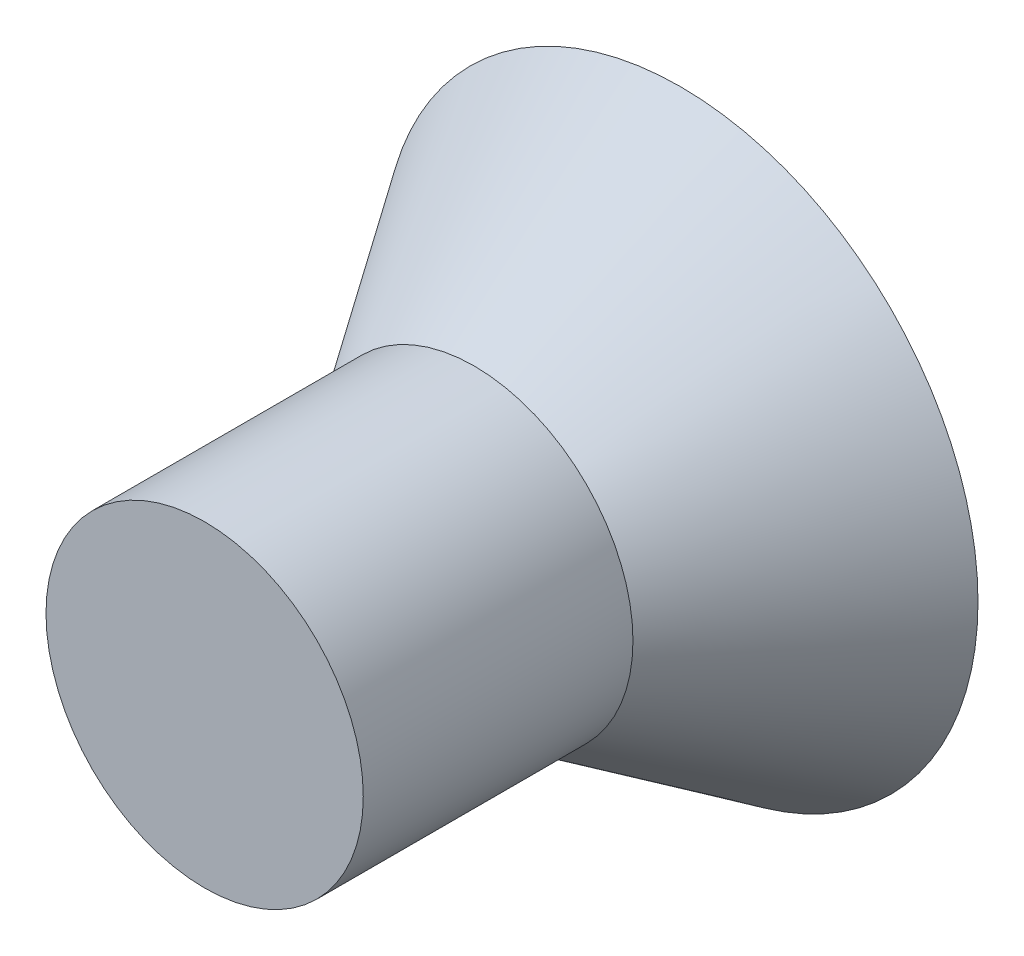
SolidWorks part; units mm, degrees
ref_plane "前视基准面" through (0, 0, 0) normal (0, 0, 1) x (1, 0, 0)
ref_plane "上视基准面" through (0, 0, 0) normal (0, 1, 0) x (1, 0, 0)
ref_plane "右视基准面" through (0, 0, 0) normal (1, 0, 0) x (0, 0, -1)
sketch "草图1" plane through (0, 0, 0) normal (0, 0, 1) x (1, 0, 0)
  circle A0 centre (0, 0) radius 2
  dimension "D1" = 4
extrude "凸台-拉伸1" add sketch "草图1" along normal blind 6
sketch "草图2" plane through (0, 0, 0) normal (0, 1, 0) x (1, 0, 0)
  line L0 (0, 0) -> (3.75, 0)
  line L1 (3.75, 0) -> (0, -5.5714)
  line L2 (0, -5.5714) -> (0, 0)
  line L3 (2, -2.6) -> (2, 0) construction
  line L4 (2, -6) -> (2, 0) construction
  dimension "D1" = 2.6
  dimension "D2" = 3.75
revolve "旋转1" add sketch "草图2" angle 360 about L2
